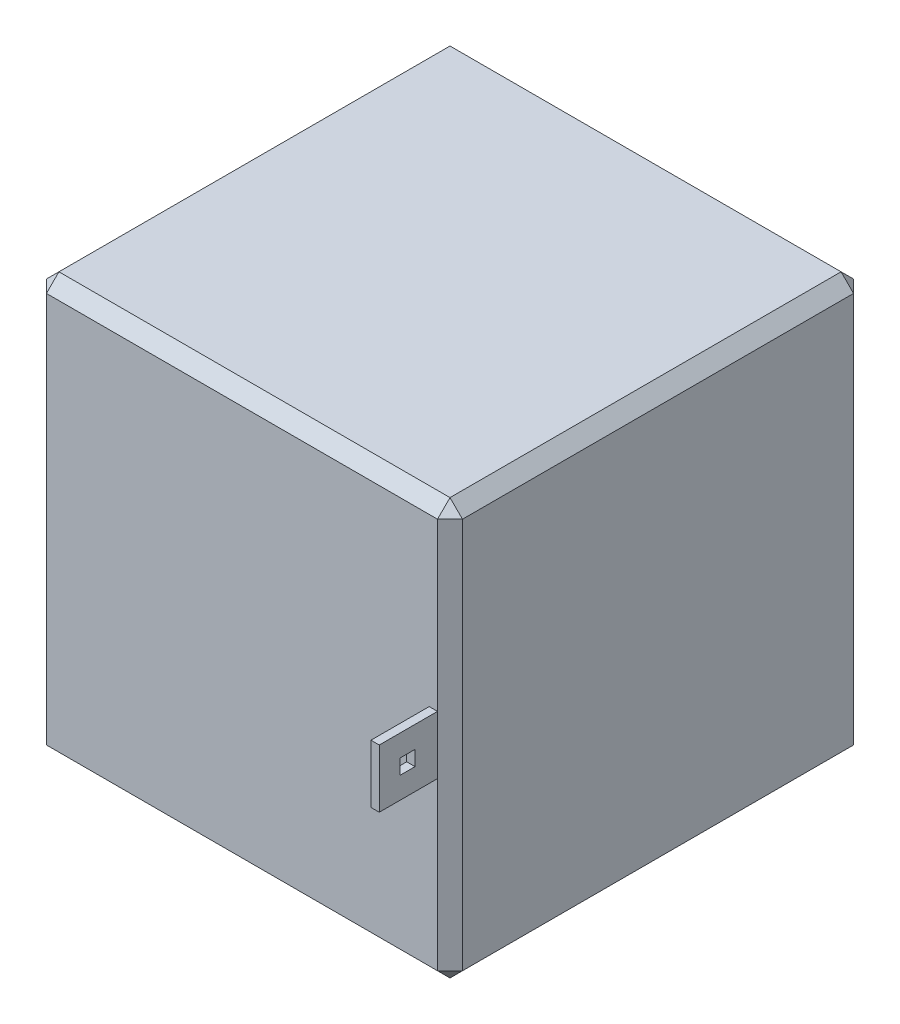
SolidWorks part; units mm, degrees
ref_plane "Front" through (0, 0, 0) normal (0, 0, 1) x (1, 0, 0)
ref_plane "Top" through (0, 0, 0) normal (0, 1, 0) x (1, 0, 0)
ref_plane "Right" through (0, 0, 0) normal (1, 0, 0) x (0, 0, -1)
sketch "Sketch1" plane through (0, 0, 0) normal (0, 0, 1) x (1, 0, 0)
  line L1 (0, 0) -> (50, 0)
  line L2 (0, 0) -> (0, 50)
  line L3 (0, 50) -> (50, 50)
  line L4 (50, 0) -> (50, 50)
  dimension "D1" = 50
extrude "Boss-Extrude1" add sketch "Sketch1" along normal blind 50
chamfer "Chamfer1" distance 1.5 angle 45 12 edges at (0, 25, 0) (0, 50, 25) (25, 50, 0) (50, 50, 25) (50, 25, 0) (0, 0, 25) (25, 0, 0) (50, 0, 25) (25, 50, 50) (50, 25, 50) (25, 0, 50) (0, 25, 50)
sketch "Sketch2" plane through (0, 0, 50) normal (0, 0, 1) x (1, 0, 0)
  line L0 (48.5, 1.5) -> (48.5, 48.5) construction
  line L1 (48.5, 21.5) -> (47.5, 21.5)
  line L2 (48.5, 21.5) -> (48.5, 28.5)
  line L3 (48.5, 28.5) -> (47.5, 28.5)
  line L4 (47.5, 21.5) -> (47.5, 28.5)
  point P6 (48.5, 25)
  dimension "D1" = 1
  dimension "D2" = 7
extrude "Boss-Extrude2" add sketch "Sketch2" along normal blind 7
sketch "Sketch3" plane through (48.5, 0, 0) normal (1, 0, 0) x (0, 0, -1)
  line L0 (-53.6, 25) -> (-57, 25) construction
  line L1 (-52.7, 24.1) -> (-54.5, 24.1)
  line L2 (-52.7, 24.1) -> (-52.7, 25.9)
  line L3 (-52.7, 25.9) -> (-54.5, 25.9)
  line L4 (-54.5, 24.1) -> (-54.5, 25.9)
  line L5 (-52.7, 24.1) -> (-54.5, 25.9) construction
  line L6 (-52.7, 25.9) -> (-54.5, 24.1) construction
  line L7 (-57, 21.5) -> (-57, 28.5) construction
  point P0 (-53.6, 25)
  dimension "D1" = 1.8
  dimension "D2" = 2.5
extrude "Cut-Extrude1" cut sketch "Sketch3" against normal through all
